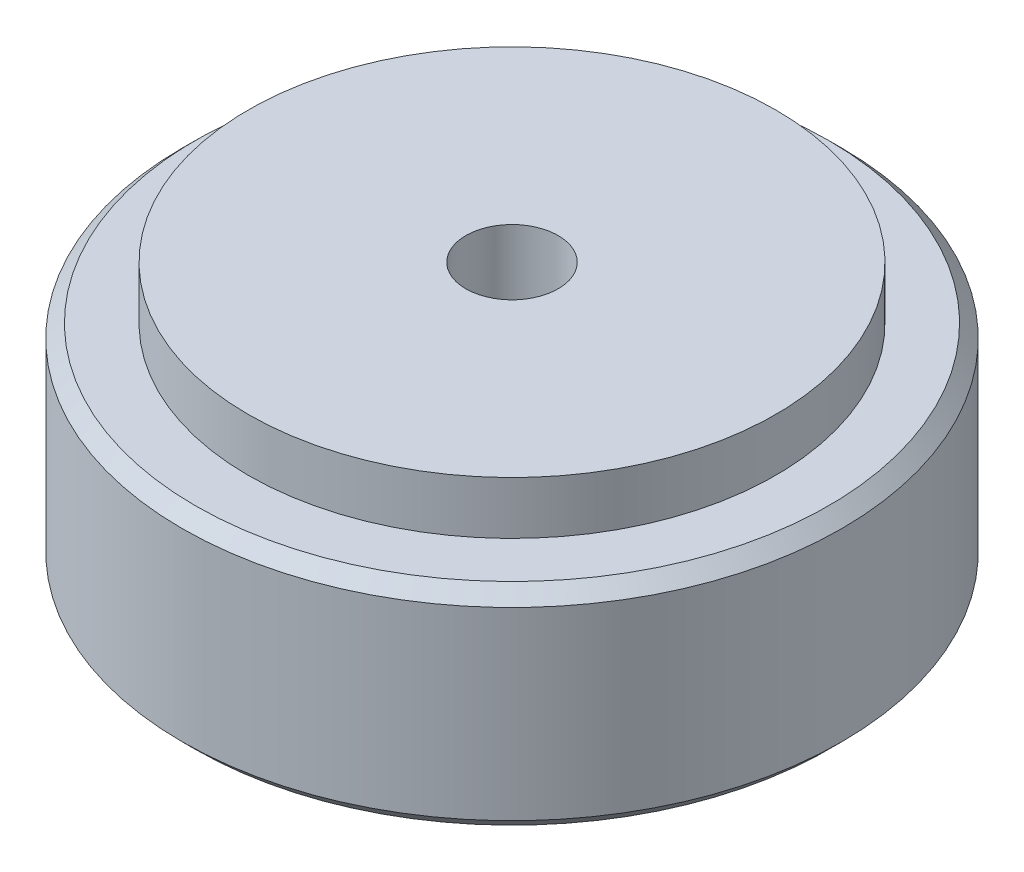
SolidWorks part; units mm, degrees
material "2024 Alloy"
ref_plane "Front Plane" through (0, 0, 0) normal (0, 0, 1) x (1, 0, 0)
ref_plane "Top Plane" through (0, 0, 0) normal (0, 1, 0) x (1, 0, 0)
ref_plane "Right Plane" through (0, 0, 0) normal (1, 0, 0) x (0, 0, -1)
sketch "Sketch1" plane through (0, 0, 0) normal (0, 1, 0) x (1, 0, 0)
  circle A0 centre (0, 0) radius 12.5
  dimension "D1" = 25
extrude "Boss-Extrude1" add sketch "Sketch1" along normal blind 8
sketch "Sketch2" plane through (0, 8, 0) normal (0, 1, 0) x (1, 0, 0)
  circle A0 centre (0, 0) radius 10
  dimension "D1" = 20
extrude "Boss-Extrude2" add sketch "Sketch2" along normal blind 2
sketch "Sketch3" plane through (0, 10, 0) normal (0, 1, 0) x (1, 0, 0)
  circle A0 centre (0, 0) radius 1.75
extrude "Cut-Extrude1" cut sketch "Sketch3" against normal up to next
sketch "Sketch4" plane through (0, 0, 0) normal (0, -1, 0) x (1, 0, 0)
  circle A0 centre (0, 0) radius 3
extrude "Cut-Extrude2" cut sketch "Sketch4" against normal blind 5
sketch "Sketch5" plane through (0, 0, 0) normal (0, -1, 0) x (1, 0, 0)
  circle A0 centre (0, 0) radius 9
  circle A1 centre (0, 0) radius 8
  dimension "D1" = 18
  dimension "D2" = 16
extrude "Boss-Extrude3" add sketch "Sketch5" along normal blind 1.5
chamfer "Chamfer1" distance 0.5 angle 45 2 edges at (0, 0, 12.5) (0, 8, 12.5)
